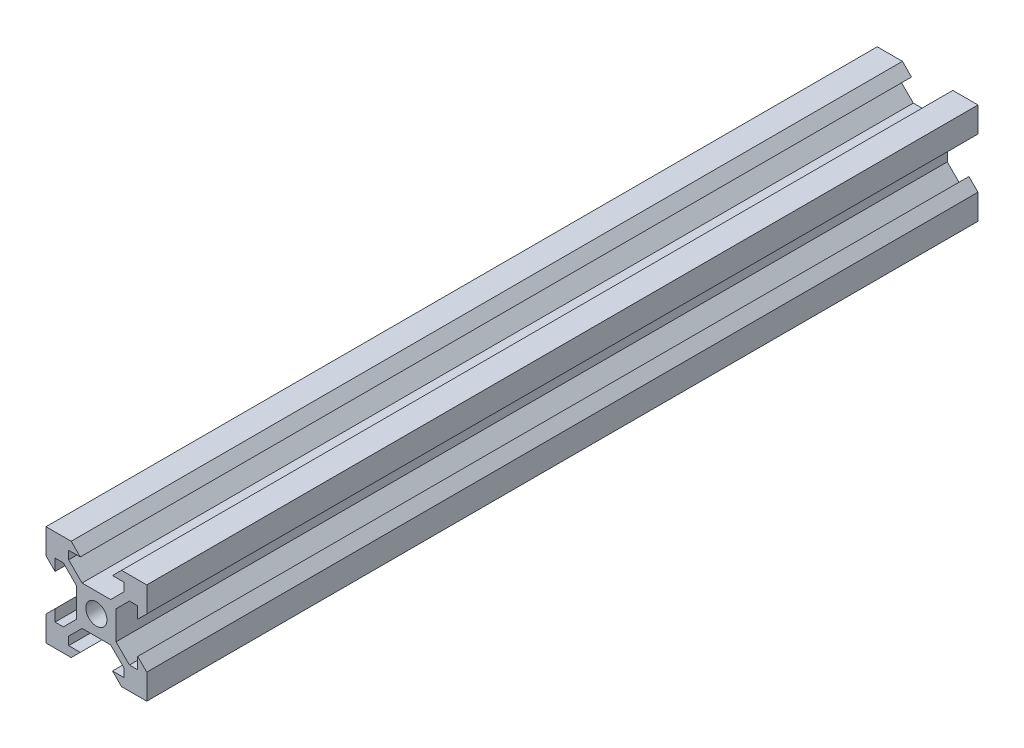
SolidWorks part; units mm, degrees
ref_plane "Front Plane" through (0, 0, 0) normal (0, 0, 1) x (1, 0, 0)
ref_plane "Top Plane" through (0, 0, 0) normal (0, 1, 0) x (1, 0, 0)
ref_plane "Right Plane" through (0, 0, 0) normal (1, 0, 0) x (0, 0, -1)
sketch "Sketch1" plane through (0, 0, 0) normal (0, 0, 1) x (1, 0, 0)
  line L0 (-10, 10) -> (-10, 5)
  line L1 (-10, 5) -> (-8.2, 3.2)
  line L2 (-8.2, 3.2) -> (-8.2, 5.4993)
  line L3 (-8.2, 5.4993) -> (-6.56, 5.4993)
  line L4 (-6.56, 5.4993) -> (-3.9007, 2.84)
  line L5 (-3.9007, 2.84) -> (-3.9007, -2.84)
  line L6 (-3.9007, -2.84) -> (-6.56, -5.4993)
  line L7 (-6.56, -5.4993) -> (-8.2, -5.4993)
  line L8 (-8.2, -5.4993) -> (-8.2, -3.2)
  line L9 (-8.2, -3.2) -> (-10, -5)
  line L10 (-10, -5) -> (-10, -10)
  line L11 (-10, -10) -> (-5, -10)
  line L12 (-5, -10) -> (-3.2, -8.2)
  line L13 (-3.2, -8.2) -> (-5.4993, -8.2)
  line L14 (-5.4993, -8.2) -> (-5.4993, -6.56)
  line L15 (-5.4993, -6.56) -> (-2.84, -3.9007)
  line L16 (-2.84, -3.9007) -> (2.84, -3.9007)
  line L17 (2.84, -3.9007) -> (5.4993, -6.56)
  line L18 (5.4993, -6.56) -> (5.4993, -8.2)
  line L19 (5.4993, -8.2) -> (3.2, -8.2)
  line L20 (3.2, -8.2) -> (5, -10)
  line L21 (5, -10) -> (10, -10)
  line L22 (10, -10) -> (10, -5)
  line L23 (10, -5) -> (8.2, -3.2)
  line L24 (8.2, -3.2) -> (8.2, -5.4993)
  line L25 (8.2, -5.4993) -> (6.56, -5.4993)
  line L26 (6.56, -5.4993) -> (3.9007, -2.84)
  line L27 (3.9007, -2.84) -> (3.9007, 2.84)
  line L28 (3.9007, 2.84) -> (6.56, 5.4993)
  line L29 (6.56, 5.4993) -> (8.2, 5.4993)
  line L30 (8.2, 5.4993) -> (8.2, 3.2)
  line L31 (8.2, 3.2) -> (10, 5)
  line L32 (10, 5) -> (10, 10)
  line L33 (10, 10) -> (5, 10)
  line L34 (5, 10) -> (3.2, 8.2)
  line L35 (3.2, 8.2) -> (5.4993, 8.2)
  line L36 (5.4993, 8.2) -> (5.4993, 6.56)
  line L37 (5.4993, 6.56) -> (2.84, 3.9007)
  line L38 (2.84, 3.9007) -> (-2.84, 3.9007)
  line L39 (-2.84, 3.9007) -> (-5.4993, 6.56)
  line L40 (-5.4993, 6.56) -> (-5.4993, 8.2)
  line L41 (-5.4993, 8.2) -> (-3.2, 8.2)
  line L42 (-3.2, 8.2) -> (-5, 10)
  line L43 (-5, 10) -> (-10, 10)
  circle A0 centre (0, 0) radius 2.1
extrude "Boss-Extrude1" add sketch "Sketch1" against normal blind 165
